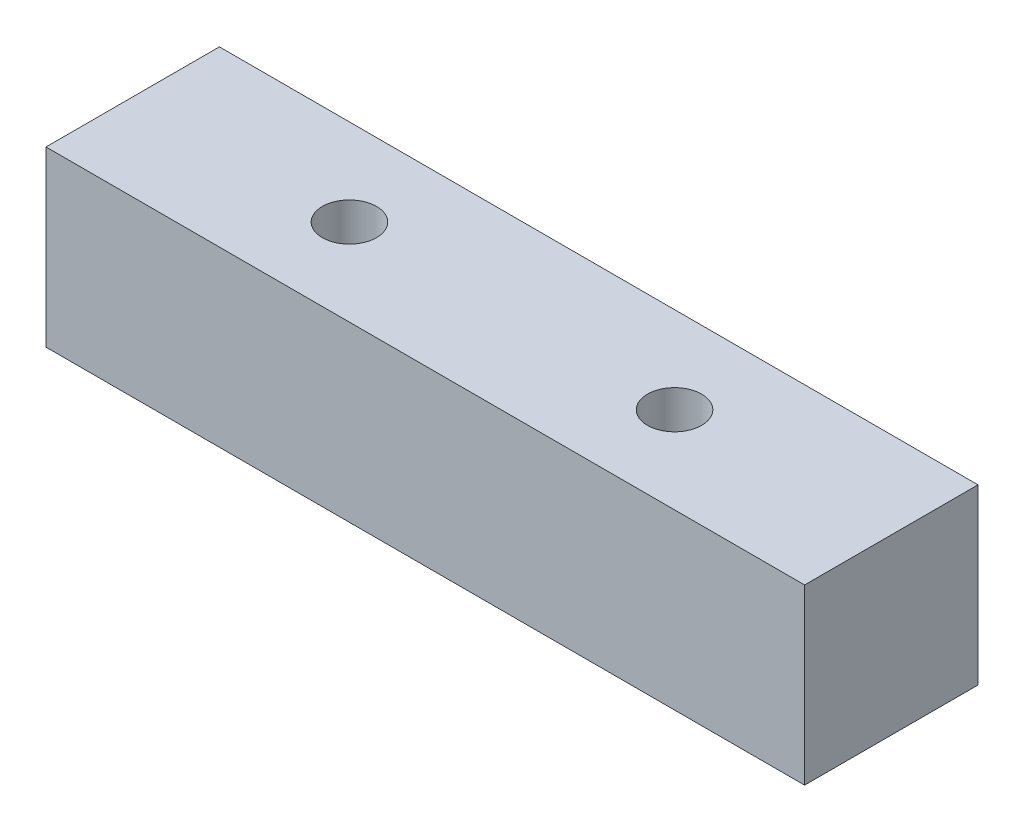
SolidWorks part; units mm, degrees
ref_plane "Front Plane" through (0, 0, 0) normal (0, 0, 1) x (1, 0, 0)
ref_plane "Top Plane" through (0, 0, 0) normal (0, 1, 0) x (1, 0, 0)
ref_plane "Right Plane" through (0, 0, 0) normal (1, 0, 0) x (0, 0, -1)
sketch "Sketch1" plane through (0, 0, 0) normal (0, 1, 0) x (1, 0, 0)
  line L0 (44.45, 0) -> (-44.45, 0) construction
  line L1 (-44.45, -10.16) -> (44.45, -10.16)
  line L2 (-44.45, -10.16) -> (-44.45, 10.16)
  line L3 (-44.45, 10.16) -> (44.45, 10.16)
  line L4 (44.45, -10.16) -> (44.45, 10.16)
  line L5 (-44.45, -10.16) -> (44.45, 10.16) construction
  line L6 (-44.45, 10.16) -> (44.45, -10.16) construction
  circle A1 centre (19.05, 0) radius 3.175
  circle A2 centre (-19.05, 0) radius 3.175
  point P0 (0, 0)
  dimension "D3" = 6.35
  dimension "D5" = 6.35
  dimension "D1" = 88.9
  dimension "D2" = 20.32
  dimension "D6" = 19.05
  dimension "D7" = 19.05
extrude "Boss-Extrude1" add sketch "Sketch1" along normal blind 20.32
